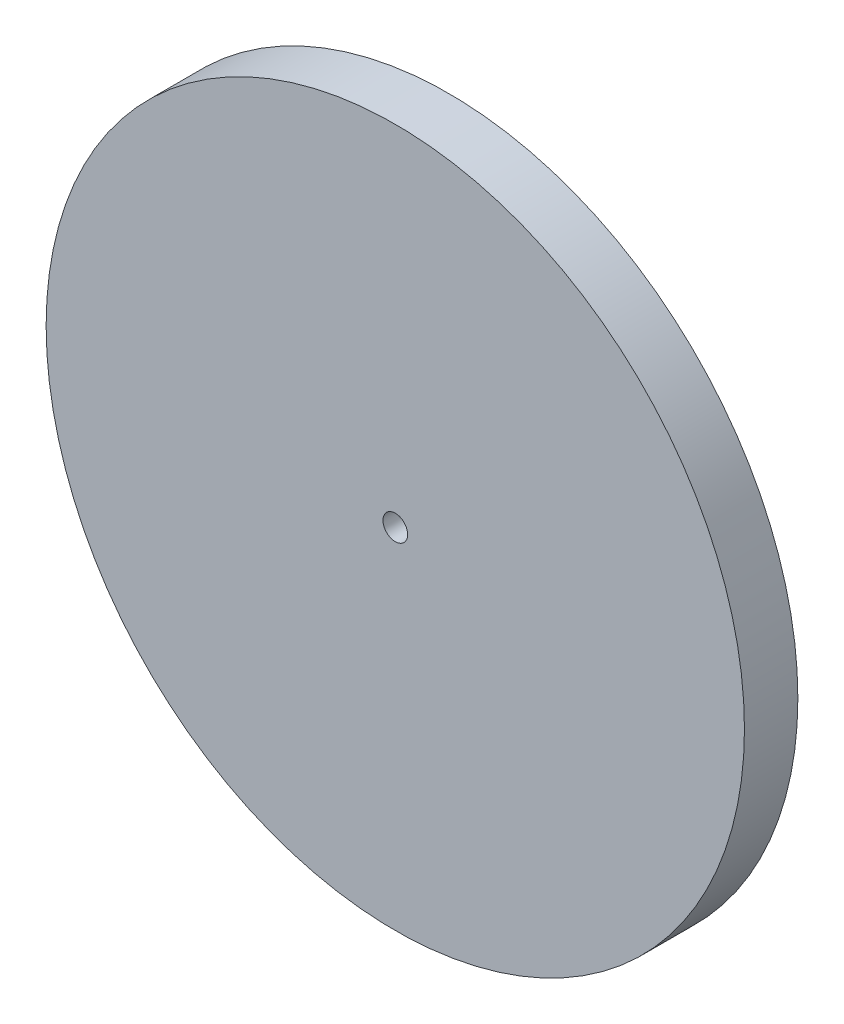
SolidWorks part; units mm, degrees
ref_plane "Ebene vorne" through (0, 0, 0) normal (0, 0, 1) x (1, 0, 0)
ref_plane "Ebene oben" through (0, 0, 0) normal (0, 1, 0) x (1, 0, 0)
ref_plane "Ebene rechts" through (0, 0, 0) normal (1, 0, 0) x (0, 0, -1)
sketch "Skizze1" plane through (0, 0, 0) normal (0, 0, 1) x (1, 0, 0)
  circle A0 centre (0, 0) radius 42.5
  dimension "D1" = 85
extrude "Aufsatz-Linear austragen1" add sketch "Skizze1" along normal blind 6.5
sketch "Skizze2" plane through (0, 0, 6.5) normal (0, 0, 1) x (1, 0, 0)
  circle A0 centre (0, 0) radius 1.5
  dimension "D1" = 3
extrude "Schnitt-Linear austragen1" cut sketch "Skizze2" against normal through all both and the other way through all
